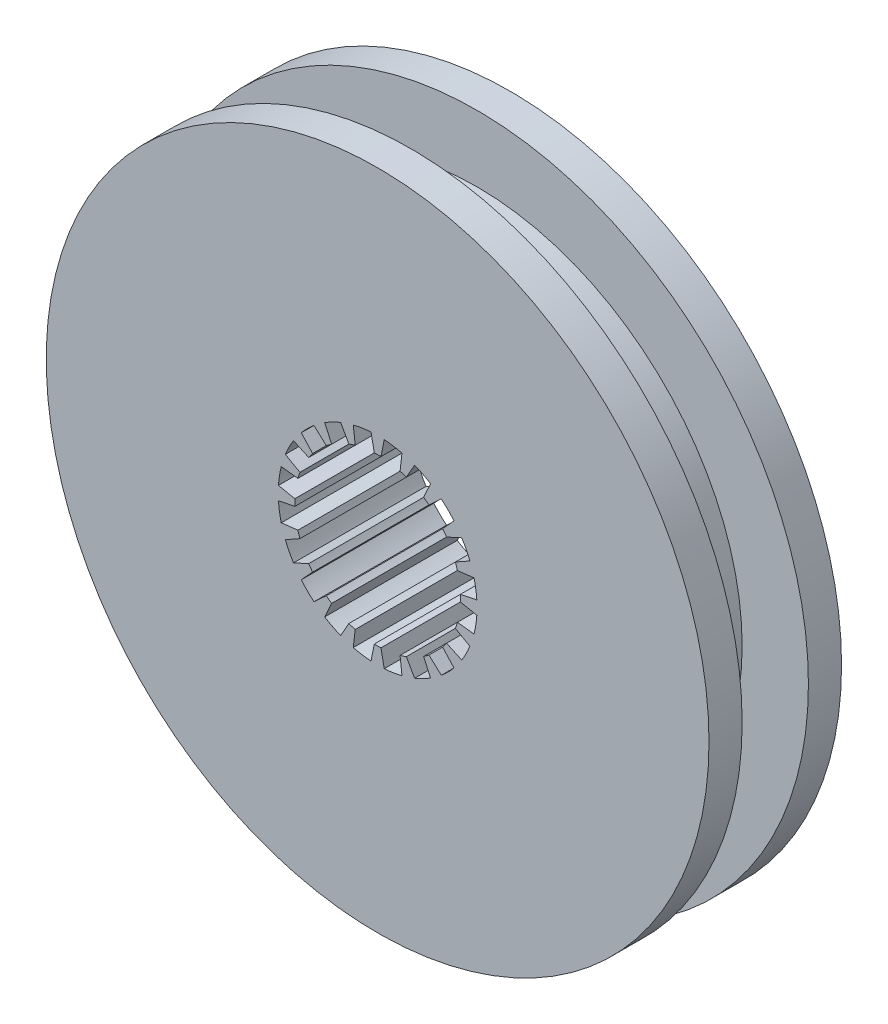
SolidWorks part; units mm, degrees
ref_plane "Front Plane" through (0, 0, 0) normal (0, 0, 1) x (1, 0, 0)
ref_plane "Top Plane" through (0, 0, 0) normal (0, 1, 0) x (1, 0, 0)
ref_plane "Right Plane" through (0, 0, 0) normal (1, 0, 0) x (0, 0, -1)
sketch "Sketch1" plane through (0, 0, 0) normal (0, 0, 1) x (1, 0, 0)
  line L0 (0, -1000) -> (0, -15) construction
  line L1 (-1, 14.9666) -> (-0.5, 12.49)
  line L2 (1, 14.9666) -> (0.5, 12.49)
  line L3 (3.6739, 14.5431) -> (3.3841, 12.0332)
  line L4 (5.576, 13.9251) -> (4.3351, 11.7242)
  line L5 (7.9881, 12.696) -> (6.9369, 10.3985)
  line L6 (9.6062, 11.5205) -> (7.7459, 9.8107)
  line L7 (11.5205, 9.6062) -> (9.8107, 7.7459)
  line L8 (12.696, 7.9881) -> (10.3985, 6.9369)
  line L9 (13.9251, 5.576) -> (11.7242, 4.3351)
  line L10 (14.5431, 3.6739) -> (12.0332, 3.3841)
  line L11 (14.9666, 1) -> (12.49, 0.5)
  line L12 (14.9666, -1) -> (12.49, -0.5)
  line L13 (14.5431, -3.6739) -> (12.0332, -3.3841)
  line L14 (13.9251, -5.576) -> (11.7242, -4.3351)
  line L15 (12.696, -7.9881) -> (10.3985, -6.9369)
  line L16 (11.5205, -9.6062) -> (9.8107, -7.7459)
  line L17 (9.6062, -11.5205) -> (7.7459, -9.8107)
  line L18 (7.9881, -12.696) -> (6.9369, -10.3985)
  line L19 (5.576, -13.9251) -> (4.3351, -11.7242)
  line L20 (3.6739, -14.5431) -> (3.3841, -12.0332)
  line L21 (1, -14.9666) -> (0.5, -12.49)
  line L22 (-1, -14.9666) -> (-0.5, -12.49)
  line L23 (-3.6739, -14.5431) -> (-3.3841, -12.0332)
  line L24 (-5.576, -13.9251) -> (-4.3351, -11.7242)
  line L25 (-7.9881, -12.696) -> (-6.9369, -10.3985)
  line L26 (-9.6062, -11.5205) -> (-7.7459, -9.8107)
  line L27 (-11.5205, -9.6062) -> (-9.8107, -7.7459)
  line L28 (-12.696, -7.9881) -> (-10.3985, -6.9369)
  line L29 (-13.9251, -5.576) -> (-11.7242, -4.3351)
  line L30 (-14.5431, -3.6739) -> (-12.0332, -3.3841)
  line L31 (-14.9666, -1) -> (-12.49, -0.5)
  line L32 (-14.9666, 1) -> (-12.49, 0.5)
  line L33 (-14.5431, 3.6739) -> (-12.0332, 3.3841)
  line L34 (-13.9251, 5.576) -> (-11.7242, 4.3351)
  line L35 (-12.696, 7.9881) -> (-10.3985, 6.9369)
  line L36 (-11.5205, 9.6062) -> (-9.8107, 7.7459)
  line L37 (-9.6062, 11.5205) -> (-7.7459, 9.8107)
  line L38 (-7.9881, 12.696) -> (-6.9369, 10.3985)
  line L39 (-5.576, 13.9251) -> (-4.3351, 11.7242)
  line L40 (-3.6739, 14.5431) -> (-3.3841, 12.0332)
  line L41 (0, -12.5) -> (0, 49000) construction
  arc A0 (14.5431, -3.6739) -> (14.9666, -1) centre (0, 0) ccw
  arc A1 (-6.9369, 10.3985) -> (-7.7459, 9.8107) centre (0, 0) ccw
  circle A2 centre (0, 0) radius 50
  arc A3 (-3.3841, 12.0332) -> (-4.3351, 11.7242) centre (0, 0) ccw
  arc A4 (0.5, 12.49) -> (-0.5, 12.49) centre (0, 0) ccw
  arc A5 (4.3351, 11.7242) -> (3.3841, 12.0332) centre (0, 0) ccw
  arc A6 (7.7459, 9.8107) -> (6.9369, 10.3985) centre (0, 0) ccw
  arc A7 (10.3985, 6.9369) -> (9.8107, 7.7459) centre (0, 0) ccw
  arc A8 (12.0332, 3.3841) -> (11.7242, 4.3351) centre (0, 0) ccw
  arc A9 (12.49, -0.5) -> (12.49, 0.5) centre (0, 0) ccw
  arc A10 (-9.8107, 7.7459) -> (-10.3985, 6.9369) centre (0, 0) ccw
  arc A11 (-11.7242, 4.3351) -> (-12.0332, 3.3841) centre (0, 0) ccw
  arc A12 (-12.49, 0.5) -> (-12.49, -0.5) centre (0, 0) ccw
  arc A13 (-12.0332, -3.3841) -> (-11.7242, -4.3351) centre (0, 0) ccw
  arc A14 (-10.3985, -6.9369) -> (-9.8107, -7.7459) centre (0, 0) ccw
  arc A15 (-7.7459, -9.8107) -> (-6.9369, -10.3985) centre (0, 0) ccw
  arc A16 (-4.3351, -11.7242) -> (-3.3841, -12.0332) centre (0, 0) ccw
  arc A17 (-0.5, -12.49) -> (0.5, -12.49) centre (0, 0) ccw
  arc A18 (3.3841, -12.0332) -> (4.3351, -11.7242) centre (0, 0) ccw
  arc A19 (6.9369, -10.3985) -> (7.7459, -9.8107) centre (0, 0) ccw
  arc A20 (9.8107, -7.7459) -> (10.3985, -6.9369) centre (0, 0) ccw
  arc A21 (11.7242, -4.3351) -> (12.0332, -3.3841) centre (0, 0) ccw
  arc A22 (14.9666, 1) -> (14.5431, 3.6739) centre (0, 0) ccw
  arc A23 (13.9251, 5.576) -> (12.696, 7.9881) centre (0, 0) ccw
  arc A24 (11.5205, 9.6062) -> (9.6062, 11.5205) centre (0, 0) ccw
  arc A25 (7.9881, 12.696) -> (5.576, 13.9251) centre (0, 0) ccw
  arc A26 (3.6739, 14.5431) -> (1, 14.9666) centre (0, 0) ccw
  arc A27 (-1, 14.9666) -> (-3.6739, 14.5431) centre (0, 0) ccw
  arc A28 (-5.576, 13.9251) -> (-7.9881, 12.696) centre (0, 0) ccw
  arc A29 (-9.6062, 11.5205) -> (-11.5205, 9.6062) centre (0, 0) ccw
  arc A30 (-12.696, 7.9881) -> (-13.9251, 5.576) centre (0, 0) ccw
  arc A31 (-14.5431, 3.6739) -> (-14.9666, 1) centre (0, 0) ccw
  arc A32 (-14.9666, -1) -> (-14.5431, -3.6739) centre (0, 0) ccw
  arc A33 (-13.9251, -5.576) -> (-12.696, -7.9881) centre (0, 0) ccw
  arc A34 (-11.5205, -9.6062) -> (-9.6062, -11.5205) centre (0, 0) ccw
  arc A35 (-7.9881, -12.696) -> (-5.576, -13.9251) centre (0, 0) ccw
  arc A36 (-3.6739, -14.5431) -> (-1, -14.9666) centre (0, 0) ccw
  arc A37 (1, -14.9666) -> (3.6739, -14.5431) centre (0, 0) ccw
  arc A38 (5.576, -13.9251) -> (7.9881, -12.696) centre (0, 0) ccw
  arc A39 (9.6062, -11.5205) -> (11.5205, -9.6062) centre (0, 0) ccw
  arc A40 (12.696, -7.9881) -> (13.9251, -5.576) centre (0, 0) ccw
  point P88 (0, 0)
  dimension "D1" = 30
  dimension "D2" = 25
  dimension "D6" = 100
  dimension "D3" = 1
  dimension "D4" = 2
  dimension "D5" = 20
extrude "Boss-Extrude1" add sketch "Sketch1" along normal mid plane 20
sketch "Sketch2" plane through (0, 0, 0) normal (1, 0, 0) x (0, 0, -1)
  line L0 (0, -1000) -> (0, 49000) construction
  line L1 (10, 50) -> (-10, 50) construction
  line L2 (-5, 50) -> (5, 50)
  line L3 (-5, 50) -> (-5, 40)
  line L4 (-5, 40) -> (5, 40)
  line L5 (5, 50) -> (5, 40)
  line L6 (-10, 50) -> (-10, -50) construction
  line L7 (10, -50) -> (10, 50) construction
  line L8 (-1000, 0) -> (49000, 0) construction
  dimension "D1" = 10
  dimension "D2" = 5
  dimension "D3" = 5
revolve "Cut-Revolve1" cut sketch "Sketch2" angle 360 about L8
